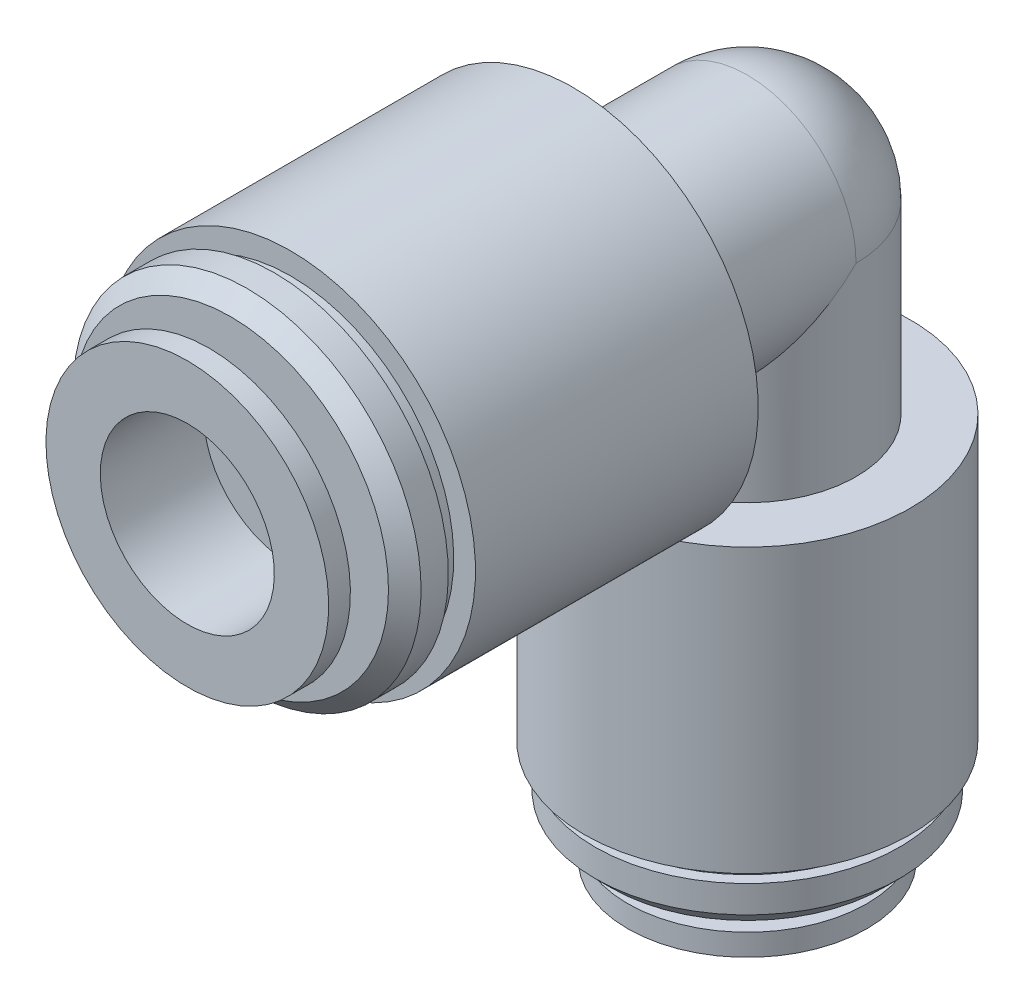
SolidWorks part; units mm, degrees
ref_plane "Спереди" through (0, 0, 0) normal (0, 0, 1) x (1, 0, 0)
ref_plane "Сверху" through (0, 0, 0) normal (0, 1, 0) x (1, 0, 0)
ref_plane "Справа" through (0, 0, 0) normal (1, 0, 0) x (0, 0, -1)
sketch "Эскиз2" plane through (0, 0, 0) normal (0, 0, 1) x (1, 0, 0)
  line L0 (0, 25) -> (0, 35)
  line L2 (0, 25) -> (5, 25)
  line L3 (5, 25) -> (5, 30)
  arc A0 (5, 30) -> (0, 35) centre (0, 30) ccw
revolve "Повернуть1" add sketch "Эскиз2" angle 360 about L0
sketch "Эскиз3" plane through (0, 0, 0) normal (0, 0, 1) x (1, 0, 0)
  arc A0 (5, 30) -> (-5, 30) centre (0, 30) ccw construction
  circle A1 centre (0, 30) radius 5
  dimension "D1" = 10
extrude "Бобышка-Вытянуть2" add sketch "Эскиз3" along normal blind 8
sketch "Эскиз4" plane through (0, 0, 8) normal (0, 0, 1) x (1, 0, 0)
  circle A0 centre (0, 30) radius 8.5
extrude "Бобышка-Вытянуть3" add sketch "Эскиз4" along normal blind 13
sketch "Эскиз5" plane through (0, 0, 0) normal (1, 0, 0) x (0, 0, -1)
  line L9 (-24.75, 23.5) -> (-24.75, 25.5)
  line L11 (-25.75, 26) -> (-25.75, 23.5)
  line L13 (-25.75, 23.5) -> (-24.75, 23.5)
  line L15 (-23.75, 25.5) -> (-23.75, 22.75)
  line L16 (-23, 22) -> (-21.75, 22)
  line L17 (-23.75, 22.75) -> (-23, 22)
  line L18 (-21.75, 22) -> (-21.75, 22.5)
  line L19 (-21.75, 22.5) -> (-21, 22.5)
  line L20 (-21, 22.5) -> (-21, 26)
  line L22 (-24.75, 25.5) -> (-23.75, 25.5)
  line L23 (-21, 30) -> (-33.2854, 30) construction
  line L24 (-21, 38.5) -> (-21, 21.5) construction
  line L25 (-25.75, 26) -> (-21, 26)
  point P13 (-23.75, 22)
  dimension "D4" = 0.75
  dimension "D5" = 0.75
sketch "Эскиз7" plane through (0, 25, 0) normal (0, -1, 0) x (1, 0, 0)
  circle A1 centre (0, 0) radius 5
extrude "Бобышка-Вытянуть4" add sketch "Эскиз7" along normal blind 3.5
sketch "Эскиз8" plane through (0, 21.5, 0) normal (0, -1, 0) x (1, 0, 0)
  circle A0 centre (0, 0) radius 7.5
  dimension "D1" = 15
extrude "Бобышка-Вытянуть6" add sketch "Эскиз8" along normal blind 13 contours A0
sketch "Эскиз9" plane through (0, 0, 0) normal (1, 0, 0) x (0, 0, -1)
  line L11 (5.5, 4.75) -> (3.5, 4.75)
  line L12 (3, 3.75) -> (5.5, 3.75)
  line L13 (5.5, 3.75) -> (5.5, 4.75)
  line L14 (3.5, 5.75) -> (6.25, 5.75)
  line L16 (7, 6.5) -> (7, 7.75)
  line L17 (6.25, 5.75) -> (7, 6.5)
  line L18 (7, 7.75) -> (6.5, 7.75)
  line L19 (6.5, 7.75) -> (6.5, 8.5)
  line L20 (6.5, 8.5) -> (3, 8.5)
  line L21 (3.5, 4.75) -> (3.5, 5.75)
  line L22 (0, 8.5) -> (0, -0.7854) construction
  line L23 (3, 3.75) -> (3, 8.5)
  point P6 (7, 5.75)
  dimension "D1" = 0.75
  dimension "D2" = 0.75
revolve "Повернуть5" add sketch "Эскиз9" angle 360 about L22
revolve "Повернуть6" add sketch "Эскиз5" angle 360 about L23
